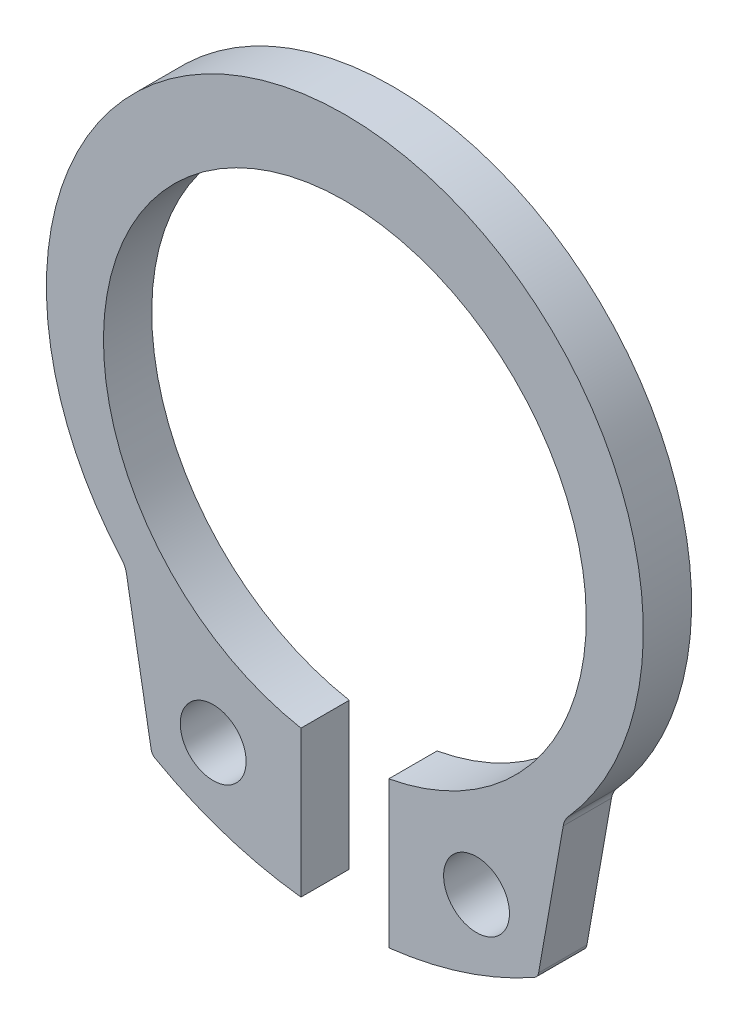
SolidWorks part; units mm, degrees
ref_plane "前视基准面" through (0, 0, 0) normal (0, 0, 1) x (1, 0, 0)
ref_plane "上视基准面" through (0, 0, 0) normal (0, 1, 0) x (1, 0, 0)
ref_plane "右视基准面" through (0, 0, 0) normal (1, 0, 0) x (0, 0, -1)
other "Configuration Table"
sketch "草图1" plane through (0, 0, 0) normal (0, 0, 1) x (1, 0, 0)
  line L0 (0, 0) -> (0, -0.4)
  line L1 (0, 0) -> (0, -11.6077) construction
  line L2 (-1, -5.8083) -> (-1, -9.143)
  line L3 (-4.975, -4.7502) -> (-4.4144, -7.9296)
  line L4 (-5, -12.5339) -> (-5, -4.6087) construction
  line L5 (-3, -6.0296) -> (-3, -12.9902) construction
  line L6 (1, -5.8083) -> (1, -9.143)
  line L7 (4.975, -4.7502) -> (4.4144, -7.9296)
  circle A6 centre (0, -0.4) radius 5.5
  arc A7 (-4.3156, -8.0692) -> (-1, -9.143) centre (0, -0.4) ccw
  circle A8 centre (-3, -7.0935) radius 0.75
  arc A9 (-4.975, -4.7502) -> (-5.093, -4.5057) centre (-5.4674, -4.837) ccw
  arc A10 (-4.4144, -7.9296) -> (-4.3156, -8.0692) centre (-4.2175, -7.8949) ccw
  circle A11 centre (3, -7.0935) radius 0.75
  arc A12 (4.4144, -7.9296) -> (4.3156, -8.0692) centre (4.2175, -7.8949) cw
  arc A13 (4.975, -4.7502) -> (5.093, -4.5057) centre (5.4674, -4.837) cw
  arc A14 (4.3156, -8.0692) -> (1, -9.143) centre (0, -0.4) cw
  arc A15 (5.093, -4.5057) -> (-5.093, -4.5057) centre (0, 0) ccw
  dimension "D3" = 11
  dimension "D4" = 1
  dimension "D5" = 17.6
  dimension "D9" = 1.5
  dimension "D10" = 0.5
  dimension "D11" = 0.2
  dimension "D2" = 0.4
  dimension "D6" = 10
  dimension "D7" = 5
  dimension "D8" = 3
extrude "凸台-拉伸1" add sketch "草图1" along normal blind 1.1 contours A13 A15 A9 L3 A10 A7 L2 A6 L6 A14 A12 L7 A11 A8
